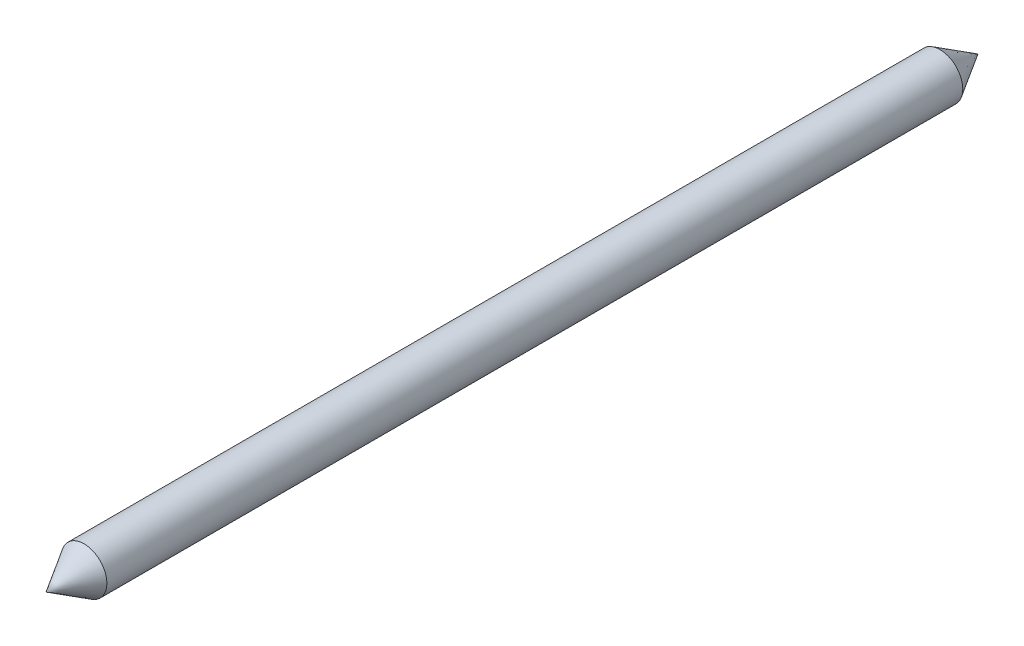
SolidWorks part; units mm, degrees
ref_plane "Front Plane" through (0, 0, 0) normal (0, 0, 1) x (1, 0, 0)
ref_plane "Top Plane" through (0, 0, 0) normal (0, 1, 0) x (1, 0, 0)
ref_plane "Right Plane" through (0, 0, 0) normal (1, 0, 0) x (0, 0, -1)
sketch "Sketch1" plane through (0, 0, 0) normal (0, 1, 0) x (1, 0, 0)
  line L0 (7.62, 142.875) -> (7.62, -142.875)
  line L1 (7.62, -142.875) -> (0, -155.575)
  line L2 (7.62, 142.875) -> (0, 155.575)
  line L3 (0, 155.575) -> (0, -155.575)
  point P2 (7.62, 0)
  dimension "D1" = 12.7
  dimension "D2" = 12.7
  dimension "D3" = 311.15
  dimension "D4" = 7.62
revolve "Revolve1" add sketch "Sketch1" angle 360 about L3
